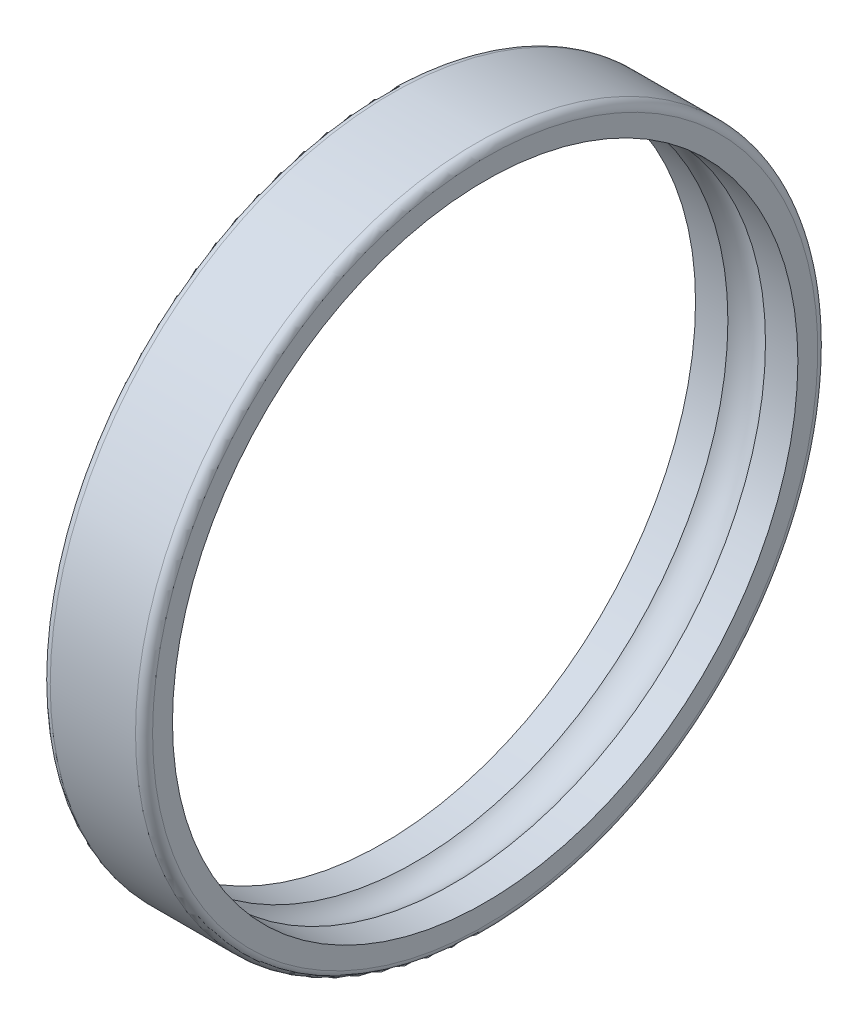
SolidWorks part; units mm, degrees
ref_plane "Plan1" through (0, 0, 0) normal (0, 0, 1) x (1, 0, 0)
ref_plane "Plan2" through (0, 0, 0) normal (0, 1, 0) x (1, 0, 0)
ref_plane "Plan3" through (0, 0, 0) normal (1, 0, 0) x (0, 0, -1)
sketch "Esquisse1" plane through (0, 0, 0) normal (0, 0, 1) x (1, 0, 0)
  line L0 (-7.7874, 0) -> (40.5484, 0) construction
  line L1 (1.5, 60) -> (16.5, 60)
  line L2 (0, 58.5) -> (0, 55)
  line L3 (18, 58.5) -> (18, 55)
  line L4 (18, 55) -> (12.3072, 55)
  line L5 (5.6928, 55) -> (0, 55)
  arc A0 (12.3072, 55) -> (5.6928, 55) centre (9, 51.25) ccw
  arc A1 (16.5, 60) -> (18, 58.5) centre (16.5, 58.5) cw
  arc A2 (0, 58.5) -> (1.5, 60) centre (1.5, 58.5) cw
  dimension "D1" = 1.5
  dimension "D4" = 5
  dimension "D2" = 60
  dimension "D3" = 51.25
  dimension "D5" = 18
  dimension "D6" = 9
  dimension "D7" = 5
revolve "Base-Révolution" add sketch "Esquisse1" angle 360 about L0
